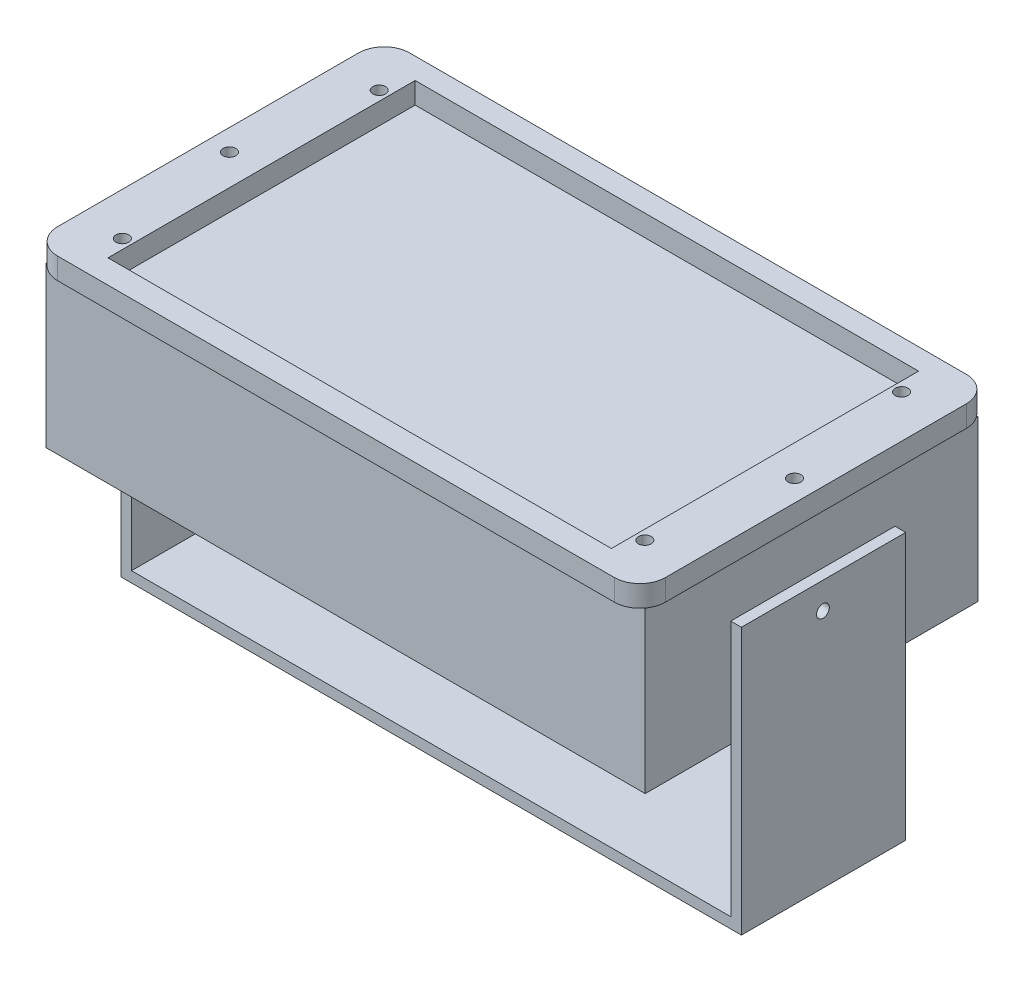
SolidWorks part; units mm, degrees
ref_plane "Front Plane" through (0, 0, 0) normal (0, 0, 1) x (1, 0, 0)
ref_plane "Top Plane" through (0, 0, 0) normal (0, 1, 0) x (1, 0, 0)
ref_plane "Right Plane" through (0, 0, 0) normal (1, 0, 0) x (0, 0, -1)
sketch "Sketch4" plane through (0, 0, 0) normal (0, 1, 0) x (1, 0, 0)
  line L0 (-118, 0) -> (118, 0) construction
  line L1 (-118, 72) -> (-118, -72) construction
  line L2 (118, 72) -> (118, -72) construction
  line L3 (-118, 72) -> (118, 72) construction
  line L4 (-118, -72) -> (118, -72) construction
  line L5 (-118, 72) -> (-174.5959, 72) construction
  line L6 (-122.45, 72) -> (-122.45, 59.6) construction
  line L7 (-122.45, 59.6) -> (-122.45, -60.8) construction
  line L8 (0, 126.6032) -> (0, -126.6032) construction
  circle A0 centre (-122.45, 59.6) radius 3
  circle A1 centre (-122.45, -60.8) radius 3
  circle A2 centre (122.45, -60.8) radius 3
  circle A3 centre (122.45, 59.6) radius 3
  point P4 (0, 0)
  point P8 (-118, 0)
  point P10 (118, 0)
  point P20 (0, 0)
  dimension "D6" = 6
  dimension "D8" = 6
  dimension "D1" = 236
  dimension "D2" = 144
  dimension "D3" = 144
  dimension "D4" = 12.4
  dimension "D5" = 4.45
  dimension "D7" = 120.4
sketch "Sketch5" plane through (0, 0, 0) normal (0, 1, 0) x (1, 0, 0)
  line L0 (118, 72) -> (118, -72) construction
  line L1 (-118, -72) -> (118, -72) construction
  line L2 (-118, 72) -> (-118, -72) construction
  line L3 (-118, 72) -> (118, 72) construction
  line L4 (118, 72) -> (118, -72)
  line L5 (-118, -72) -> (118, -72)
  line L6 (-118, 72) -> (-118, -72)
  line L7 (-118, 72) -> (118, 72)
  line L8 (-122.45, 59.6) -> (-122.45, -60.8) construction
  line L9 (-122.45, 59.6) -> (-122.45, -60.8) construction
  line L10 (-122.45, -0.6) -> (-142.45, -0.6) construction
  line L11 (0, 126.6032) -> (0, -126.6032) construction
  line L12 (0, 126.6032) -> (0, -126.6032) construction
  line L13 (-142.45, 69.9) -> (-142.45, -71.1)
  line L14 (142.45, 69.9) -> (142.45, -71.1)
  line L15 (-130.45, 81.9) -> (130.45, 81.9)
  line L16 (-130.45, -83.1) -> (130.45, -83.1)
  circle A0 centre (-122.45, 59.6) radius 3 construction
  circle A1 centre (-122.45, -60.8) radius 3 construction
  circle A2 centre (122.45, -60.8) radius 3 construction
  circle A3 centre (122.45, 59.6) radius 3 construction
  circle A4 centre (-122.45, 59.6) radius 3
  circle A5 centre (-122.45, -60.8) radius 3
  circle A6 centre (122.45, -60.8) radius 3
  circle A7 centre (122.45, 59.6) radius 3
  arc A8 (142.45, -71.1) -> (130.45, -83.1) centre (130.45, -71.1) cw
  arc A9 (142.45, 69.9) -> (130.45, 81.9) centre (130.45, 69.9) ccw
  arc A10 (-142.45, -71.1) -> (-130.45, -83.1) centre (-130.45, -71.1) ccw
  arc A11 (-142.45, 69.9) -> (-130.45, 81.9) centre (-130.45, 69.9) cw
  circle A12 centre (-132.45, -0.6) radius 3
  circle A13 centre (132.45, -0.6) radius 3
  point P24 (-142.45, -0.6)
  point P29 (142.45, -83.1)
  point P32 (142.45, 81.9)
  point P35 (-142.45, -83.1)
  point P38 (-142.45, 81.9)
  dimension "D3" = 12
  dimension "D4" = 6
  dimension "D1" = 20
  dimension "D2" = 165
extrude "Boss-Extrude1" add sketch "Sketch5" along normal blind 10
sketch "Sketch7" plane through (0, 0, 0) normal (0, -1, 0) x (1, 0, 0)
  line L0 (0, -126.6032) -> (0, 126.6032) construction
  line L1 (0, -126.6032) -> (0, 126.6032) construction
  line L2 (-135.45, 0.6) -> (-140.45, 0.6) construction
  line L3 (-140.45, 78.6) -> (-140.45, -77.4)
  line L4 (140.45, 78.6) -> (140.45, -77.4)
  line L5 (-140.45, 78.6) -> (140.45, 78.6)
  line L6 (-140.45, -77.4) -> (140.45, -77.4)
  circle A0 centre (132.45, 0.6) radius 3 construction
  circle A1 centre (-132.45, 0.6) radius 3 construction
  circle A2 centre (132.45, 0.6) radius 3
  circle A3 centre (-132.45, 0.6) radius 3
  point P13 (-140.45, 0.6)
  dimension "D1" = 5
  dimension "D2" = 156
extrude "Boss-Extrude2" add sketch "Sketch7" along normal blind 75
sketch "Sketch8" plane through (-140.45, 0, 0) normal (-1, 0, 0) x (0, 0, 1)
  line L0 (0, 0) -> (0.6, -75) construction
  line L1 (78.6, -75) -> (-77.4, -75) construction
  circle A0 centre (0.3, -37.5) radius 3
  dimension "D1" = 6
ref_plane "Plane1" through (0, -145, 0) normal (0, -1, 0) x (-1, 0, 0)
sketch "Sketch9" plane through (0, -145, 0) normal (0, -1, 0) x (-1, 0, 0)
  line L0 (140.45, -77.7332) -> (140.45, 76.5332) construction
  line L1 (-140.45, 76.5332) -> (-140.45, -77.7332) construction
  line L2 (140.45, -77.7332) -> (140.45, 76.5332)
  line L3 (-140.45, 76.5332) -> (-140.45, -77.7332)
  line L4 (-180.7119, 0) -> (180.7119, 0) construction
  line L6 (0, 126.6032) -> (0, -126.6032) construction
  line L7 (0, 126.6032) -> (0, -126.6032) construction
  line L8 (-145.45, 38.5) -> (-145.45, -38.5)
  line L9 (145.45, 38.5) -> (145.45, -38.5)
  line L10 (-145.45, 38.5) -> (145.45, 38.5)
  line L11 (-145.45, -38.5) -> (145.45, -38.5)
  point P4 (-145.45, 0)
  point P8 (0, 0)
  point P9 (145.45, 0)
  point P16 (-145.45, 0)
  dimension "D1" = 5
  dimension "D2" = 5
  dimension "D3" = 77
extrude "Boss-Extrude3" add sketch "Sketch9" along normal blind 5 separate body contours L8 L11 L3 L10 | L3 L11 L2 L10 | L2 L11 L9 L10
sketch "Sketch10" plane through (0, -145, 0) normal (0, 1, 0) x (1, 0, 0)
  line L2 (-140.45, -77.7332) -> (-140.45, 76.5332) construction
  line L3 (-140.45, -38.5) -> (-140.45, 38.5)
  line L4 (145.45, -38.5) -> (145.45, 38.5)
  line L5 (145.45, 38.5) -> (-145.45, 38.5)
  line L6 (-145.45, 38.5) -> (-145.45, -38.5)
  line L7 (-145.45, -38.5) -> (145.45, -38.5)
  line L8 (145.45, -38.5) -> (145.45, 38.5)
  line L10 (-145.45, 38.5) -> (-145.45, -38.5)
  line L11 (-145.45, -38.5) -> (-140.45, -38.5)
  line L12 (-140.45, 38.5) -> (-145.45, 38.5)
  line L14 (140.45, 77.4) -> (140.45, -78.6) construction
  line L15 (140.45, 38.5) -> (140.45, -38.5)
  line L16 (145.45, -38.5) -> (140.45, -38.5)
  line L17 (145.45, 38.5) -> (140.45, 38.5)
  line L18 (145.45, 38.5) -> (-145.45, 38.5) construction
  dimension "D1" = 0
extrude "Boss-Extrude5" add sketch "Sketch10" along normal blind 120
sketch "Sketch11" plane through (-145.45, 0, 0) normal (-1, 0, 0) x (0, 0, 1)
  circle A0 centre (0.3, -37.5) radius 3 construction
  circle A1 centre (0.3, -37.5) radius 3
extrude "Cut-Extrude1" cut sketch "Sketch11" against normal blind 1011
ref_plane "Plane2" through (155.45, 0, 0) normal (1, 0, 0) x (0, 0, -1)
sketch "Sketch12" plane through (155.45, 0, 0) normal (1, 0, 0) x (0, 0, -1)
  line L0 (-177.1885, -87.5) -> (100.1885, -87.5)
  line L1 (-0.3, -37.5) -> (-0.3, -87.5) construction
  line L4 (-38.5, -25) -> (-38.5, -150)
  line L5 (-38.5, -150) -> (38.5, -150)
  line L6 (38.5, -150) -> (38.5, -25)
  line L7 (38.5, -25) -> (-38.5, -25)
  line L8 (-38.5, -25) -> (-38.5, -150)
  line L9 (-38.5, -150) -> (38.5, -150)
  line L10 (38.5, -150) -> (38.5, -25)
  line L11 (38.5, -25) -> (-38.5, -25)
  circle A0 centre (-0.3, -37.5) radius 3 construction
  circle A1 centre (-0.3, -37.5) radius 3 construction
  point P10 (-38.5, -87.5)
  dimension "D1" = 0
ref_plane "Plane3" through (0, -160, 0) normal (0, -1, 0) x (-1, 0, 0)
sketch "Sketch13" plane through (0, -160, 0) normal (0, -1, 0) x (-1, 0, 0)
  line L4 (-145.45, 38.5) -> (-145.45, -38.5)
  line L5 (-145.45, -38.5) -> (145.45, -38.5)
  line L6 (145.45, -38.5) -> (145.45, 38.5)
  line L7 (145.45, 38.5) -> (-145.45, 38.5)
  line L8 (-145.45, 38.5) -> (-145.45, -38.5)
  line L9 (-145.45, -38.5) -> (145.45, -38.5)
  line L10 (145.45, -38.5) -> (145.45, 38.5)
  line L11 (145.45, 38.5) -> (-145.45, 38.5)
  dimension "D1" = 0
